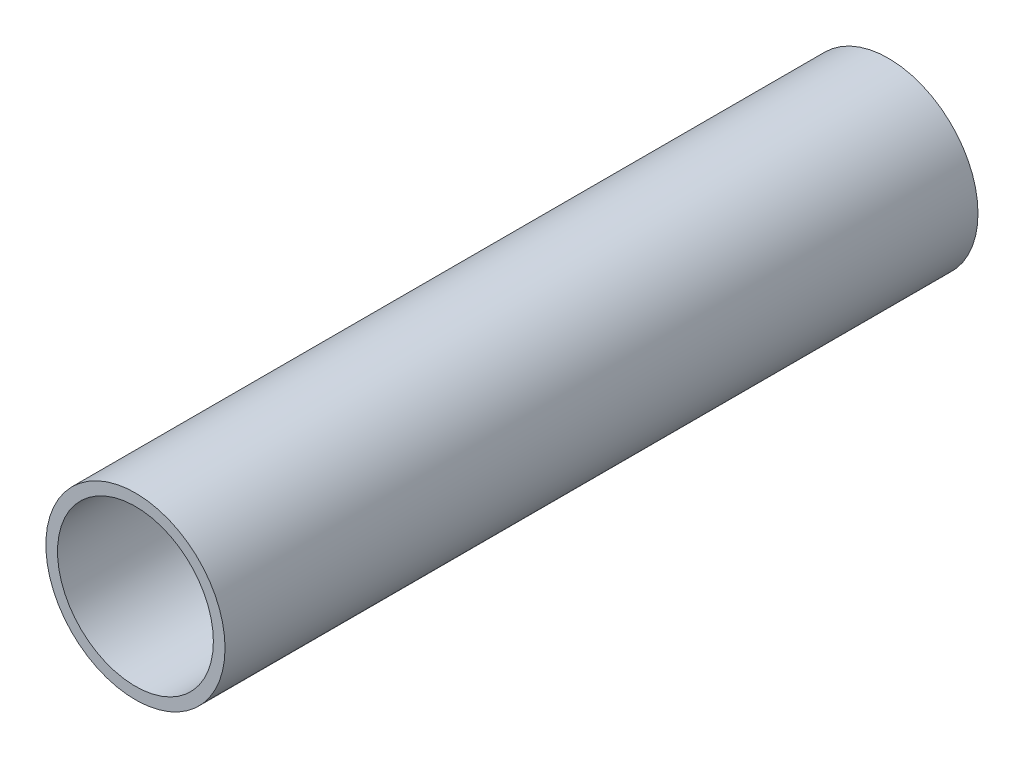
SolidWorks part; units mm, degrees
ref_plane "Front Plane" through (0, 0, 0) normal (0, 0, 1) x (1, 0, 0)
ref_plane "Top Plane" through (0, 0, 0) normal (0, 1, 0) x (1, 0, 0)
ref_plane "Right Plane" through (0, 0, 0) normal (1, 0, 0) x (0, 0, -1)
sketch "Sketch1" plane through (0, 0, 0) normal (0, 0, 1) x (1, 0, 0)
  circle A0 centre (0, 0) radius 30.226
  circle A1 centre (0, 0) radius 26.289
  dimension "D1" = 60.452
  dimension "D2" = 52.578
extrude "Boss-Extrude1" add sketch "Sketch1" along normal blind 254
